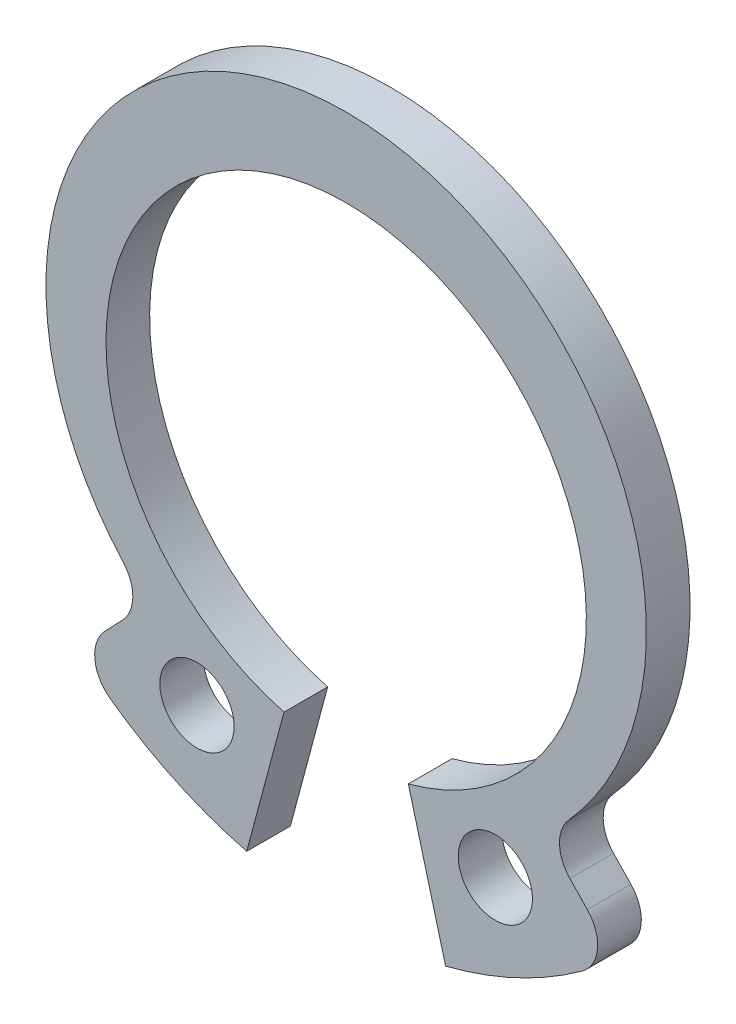
SolidWorks part; units mm, degrees
ref_plane "Plan1" through (0, 0, 0) normal (0, 0, 1) x (1, 0, 0)
ref_plane "Plan2" through (0, 0, 0) normal (0, 1, 0) x (1, 0, 0)
ref_plane "Plan3" through (0, 0, 0) normal (1, 0, 0) x (0, 0, -1)
sketch "Esquisse1" plane through (0, 0, 0) normal (0, 0, 1) x (1, 0, 0)
  line L0 (0, 0) -> (2.2776, -8.5001) construction
  line L1 (0, 0) -> (0, -67.082) construction
  line L2 (5.1223, -5.3383) -> (5.5221, -5.755)
  line L3 (1.4235, -5.3126) -> (2.2776, -8.5001)
  line L4 (-1.4235, -5.3126) -> (-2.2776, -8.5001)
  line L5 (-5.1223, -5.3383) -> (-5.5221, -5.755)
  line L6 (1.4235, -5.3126) -> (5.4078, -7.0316) construction
  line L7 (0, 0) -> (0, 5.5) construction
  line L8 (0, 5.5) -> (0, 7.3) construction
  arc A0 (1.4235, -5.3126) -> (-1.4235, -5.3126) centre (0, 0) ccw
  arc A1 (2.2776, -8.5001) -> (5.4078, -7.0316) centre (0, 0.425) ccw
  arc A2 (5.1045, -4.1804) -> (-5.1045, -4.1804) centre (0, 0.425) ccw
  arc A3 (-5.4078, -7.0316) -> (-2.2776, -8.5001) centre (0, 0.425) ccw
  arc A4 (-5.1045, -4.1804) -> (-5.1223, -5.3383) centre (-5.7356, -4.7498) cw
  arc A5 (5.1045, -4.1804) -> (5.1223, -5.3383) centre (5.7356, -4.7498) ccw
  circle A6 centre (3.4157, -6.1721) radius 0.85
  circle A7 centre (-3.4157, -6.1721) radius 0.85
  arc A8 (-5.4078, -7.0316) -> (-5.5221, -5.755) centre (-4.9088, -6.3435) cw
  arc A9 (5.4078, -7.0316) -> (5.5221, -5.755) centre (4.9088, -6.3435) ccw
  point P22 (-6.1618, -6.4217)
  dimension "D1" = 11
  dimension "D2" = 3.3
  dimension "D3" = 1.8
  dimension "D8" = 1.7
  dimension "D4" = 0.425
  dimension "D5" = 4.25
  dimension "a" = 15
extrude "Base-Extrusion" add sketch "Esquisse1" along normal blind 1
equation "\"R@Esquisse1\" = \"D8@Esquisse1\"/2"
equation "\"D4@Esquisse1\"=\"R@Esquisse1\"/2"
equation "\"D5@Esquisse1\"=\"D8@Esquisse1\"*2.5"
